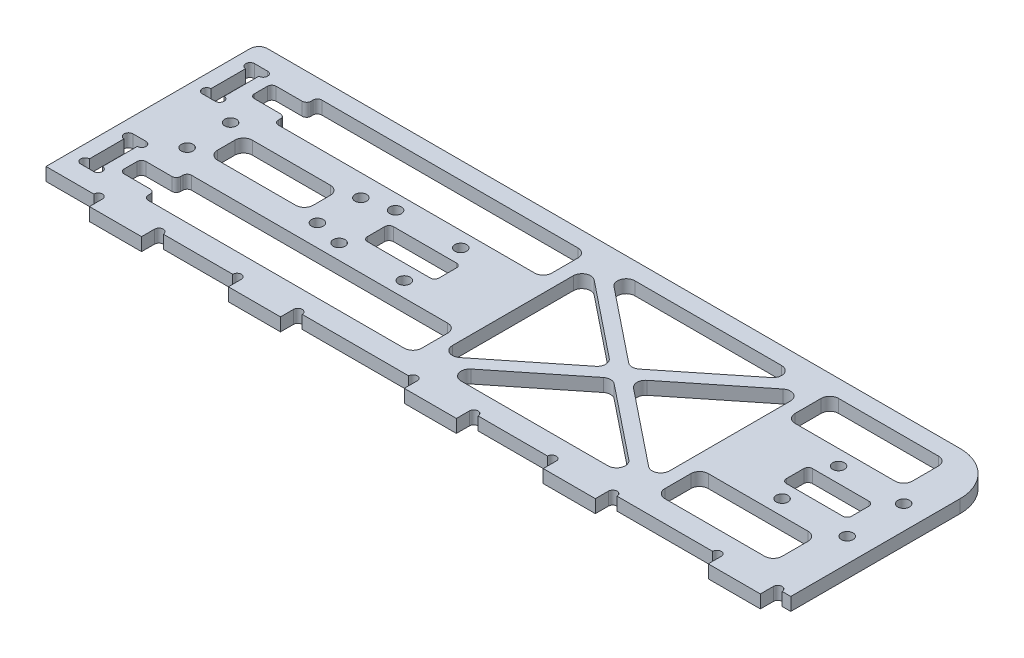
SolidWorks part; units mm, degrees
material "碳纤维"
ref_plane "前视基准面" through (0, 0, 0) normal (0, 0, 1) x (1, 0, 0)
ref_plane "上视基准面" through (0, 0, 0) normal (0, 1, 0) x (1, 0, 0)
ref_plane "右视基准面" through (0, 0, 0) normal (1, 0, 0) x (0, 0, -1)
sketch "草图1" plane through (0, 0, 0) normal (0, 1, 0) x (1, 0, 0)
  line L0 (-74, -10) -> (-12, -10)
  line L1 (-80, -24) -> (80, -24)
  line L2 (-80, -24) -> (-80, 24)
  line L3 (-80, 24) -> (80, 24)
  line L4 (80, -24) -> (80, 24)
  line L5 (0, 24) -> (0, -24) construction
  line L6 (-80, 0) -> (80, 0) construction
  line L7 (-74, 20) -> (-12, 20)
  line L8 (-74, 20) -> (-74, 10)
  line L9 (-74, 10) -> (-12, 10)
  line L10 (-12, 20) -> (-12, 10)
  line L11 (-43, 10) -> (-43, 20) construction
  line L12 (-74, 15) -> (-12, 15) construction
  line L13 (-40.5, 3) -> (-24, 3)
  line L14 (-40.5, 3) -> (-40.5, -3)
  line L15 (-40.5, -3) -> (-24, -3)
  line L16 (-24, 3) -> (-24, -3)
  line L17 (-32.25, -3) -> (-32.25, 3) construction
  line L18 (-40.5, 0) -> (-24, 0) construction
  line L19 (-12, -20) -> (-12, -10)
  line L20 (-74, -20) -> (-12, -20)
  line L21 (-74, -20) -> (-74, -10)
  line L22 (71, -10) -> (44, -10)
  line L23 (71, 20) -> (44, 20)
  line L24 (71, 20) -> (71, 10)
  line L25 (71, 10) -> (44, 10)
  line L26 (44, 20) -> (44, 10)
  line L27 (57.5, 10) -> (57.5, 20) construction
  line L28 (71, 15) -> (44, 15) construction
  line L29 (71, 3) -> (56, 3)
  line L30 (71, 3) -> (71, -3)
  line L31 (71, -3) -> (56, -3)
  line L32 (56, 3) -> (56, -3)
  line L33 (63.5, -3) -> (63.5, 3) construction
  line L34 (71, 0) -> (56, 0) construction
  line L35 (44, -20) -> (44, -10)
  line L36 (71, -20) -> (44, -20)
  line L37 (71, -20) -> (71, -10)
  point P0 (0, 0)
  point P138 (-43, 15)
  point P147 (63.5, 0)
  point P195 (-32.25, 0)
  point P297 (57.5, 15)
  dimension "D1" = 160
  dimension "D2" = 48
  dimension "D3" = 62
  dimension "D4" = 6
  dimension "D5" = 4
  dimension "D6" = 10
  dimension "D7" = 33.5
  dimension "D8" = 6
  dimension "D9" = 9
  dimension "D10" = 27
  dimension "D11" = 12
  dimension "D12" = 12
extrude "凸台-拉伸1" add sketch "草图1" along normal blind 3
sketch "草图2" plane through (0, 3, 0) normal (0, 1, 0) x (1, 0, 0)
  line L0 (80, 0) -> (-48, 0) construction
  line L1 (80, -24) -> (80, 24) construction
  line L2 (44, 15) -> (-12, 15) construction
  line L3 (44, 20) -> (44, 10) construction
  line L4 (-12, 10) -> (-12, 20) construction
  line L5 (16, 15) -> (16, 0) construction
  line L6 (67, 10) -> (67, -10) construction
  line L7 (44, 10) -> (71, 10) construction
  line L8 (71, -10) -> (44, -10) construction
  circle A0 centre (74.5, 6.5) radius 1.35
  circle A1 centre (59.5, 6.5) radius 1.35
  circle A2 centre (59.5, -6.5) radius 1.35
  circle A3 centre (74.5, -6.5) radius 1.35
  circle A4 centre (-42.5, -6.5) radius 1.35
  circle A5 centre (-27.5, -6.5) radius 1.35
  circle A6 centre (-27.5, 6.5) radius 1.35
  circle A7 centre (-42.5, 6.5) radius 1.35
  dimension "D3" = 2.7
  dimension "D1" = 15
  dimension "D2" = 13
  dimension "D4" = 51
extrude "切除-拉伸1" cut sketch "草图2" against normal through all
sketch "草图3" plane through (0, 3, 0) normal (0, 1, 0) x (1, 0, 0)
  line L0 (-80, 24) -> (-80, -24) construction
  line L1 (80, -24) -> (-80, -24)
  line L2 (80, -24) -> (80, -25)
  line L3 (80, -25) -> (-80, -25)
  line L4 (-80, -24) -> (-80, -25)
  line L5 (0, -25) -> (0, -24) construction
  line L6 (80, -24.5) -> (-80, -24.5) construction
  point P196 (0, -24.5)
  dimension "D1" = 1
extrude "凸台-拉伸2" add sketch "草图3" against normal blind 3
sketch "草图5" plane through (0, 3, 0) normal (0, 1, 0) x (1, 0, 0)
  line L0 (80, 24) -> (-80, 24) construction
  line L1 (-80, -25) -> (-85, -25)
  line L2 (-80, -25) -> (-80, 24)
  line L3 (-80, 24) -> (-85, 24)
  line L4 (-85, -25) -> (-85, 24)
  line L5 (-82.5, 24) -> (-82.5, -25) construction
  line L6 (-80, -0.5) -> (-85, -0.5) construction
  point P104 (-82.5, -0.5)
  dimension "D1" = 5
extrude "凸台-拉伸4" add sketch "草图5" against normal up to surface (3 mm away) up to face at (-42.5, 0, 7.85)
sketch "草图6" plane through (0, 3, 0) normal (0, 1, 0) x (1, 0, 0)
  line L0 (-74, -10) -> (-74, -20) construction
  line L1 (-74, -17.5) -> (-82, -17.5)
  line L2 (-74, -17.5) -> (-74, -12.5)
  line L3 (-74, -12.5) -> (-82, -12.5)
  line L4 (-82, -17.5) -> (-82, -12.5)
  line L5 (-78, -12.5) -> (-78, -17.5) construction
  line L6 (-74, -15) -> (-82, -15) construction
  line L7 (-12, -15) -> (-12, 15) construction
  line L8 (-12, -20) -> (-12, -10) construction
  line L9 (-12, 10) -> (-12, 20) construction
  line L10 (-12, 0) -> (-85, 0) construction
  line L12 (-74, 12.5) -> (-82, 12.5)
  line L13 (-82, 17.5) -> (-82, 12.5)
  line L14 (-74, 17.5) -> (-82, 17.5)
  line L15 (-74, 17.5) -> (-74, 12.5)
  line L16 (-85, 24) -> (-85, -25) construction
  point P96 (-78, -15)
  dimension "D1" = 8
  dimension "D2" = 5
extrude "切除-拉伸2" cut sketch "草图6" against normal through all
sketch "草图7" plane through (0, 3, 0) normal (0, 1, 0) x (1, 0, 0)
  line L0 (-85, -25) -> (80, -25) construction
  line L1 (76, -25) -> (64, -25)
  line L2 (76, -25) -> (76, -28)
  line L3 (76, -28) -> (64, -28)
  line L4 (64, -25) -> (64, -28)
  line L5 (70, -28) -> (70, -25) construction
  line L6 (76, -26.5) -> (64, -26.5) construction
  line L7 (80, -25) -> (80, 24) construction
  line L8 (44, -15) -> (-12, -15) construction
  line L9 (44, -10) -> (44, -20) construction
  line L10 (-12, -20) -> (-12, -10) construction
  line L11 (16, -15) -> (16, -25) construction
  line L12 (-6, -28) -> (6, -28)
  line L13 (38, -25) -> (26, -25)
  line L14 (38, -25) -> (38, -28)
  line L15 (38, -28) -> (26, -28)
  line L16 (26, -25) -> (26, -28)
  line L17 (32, -28) -> (32, -25) construction
  line L18 (38, -26.5) -> (26, -26.5) construction
  line L19 (6, -25) -> (6, -28)
  line L20 (-6, -25) -> (6, -25)
  line L21 (-6, -25) -> (-6, -28)
  line L22 (-56.5, -25) -> (-56.5, 24) construction
  line L23 (-85, -25) -> (80, -25) construction
  line L24 (80, 24) -> (-85, 24) construction
  line L25 (-85, 24) -> (-85, -25) construction
  line L26 (-78.5, -28) -> (-66.5, -28)
  line L27 (-34.5, -25) -> (-46.5, -25)
  line L28 (-34.5, -25) -> (-34.5, -28)
  line L29 (-34.5, -28) -> (-46.5, -28)
  line L30 (-46.5, -25) -> (-46.5, -28)
  line L31 (-40.5, -28) -> (-40.5, -25) construction
  line L32 (-34.5, -26.5) -> (-46.5, -26.5) construction
  line L33 (-66.5, -25) -> (-66.5, -28)
  line L34 (-78.5, -25) -> (-66.5, -25)
  line L35 (-78.5, -25) -> (-78.5, -28)
  point P76 (70, -26.5)
  point P93 (32, -26.5)
  point P138 (-40.5, -26.5)
  dimension "D1" = 12
  dimension "D2" = 10
  dimension "D3" = 3
  dimension "D4" = 12
  dimension "D5" = 3
  dimension "D6" = 20
  dimension "D7" = 28.5
  dimension "D8" = 12
  dimension "D9" = 20
extrude "凸台-拉伸5" add sketch "草图7" against normal up to surface (3 mm away) up to face at (-60.5, 0, 15)
sketch "草图9" plane through (0, 3, 0) normal (0, 1, 0) x (1, 0, 0)
  line L0 (-85, 24) -> (-85, -25) construction
  line L1 (-85, -20.5) -> (-88, -20.5)
  line L2 (-85, -20.5) -> (-85, -8.5)
  line L3 (-85, -8.5) -> (-88, -8.5)
  line L4 (-88, -20.5) -> (-88, -8.5)
  line L5 (-86.5, -8.5) -> (-86.5, -20.5) construction
  line L6 (-85, -14.5) -> (-88, -14.5) construction
  line L7 (-85, -0.5) -> (80, -0.5) construction
  line L8 (80, -25) -> (80, 24) construction
  line L9 (-85, 7.5) -> (-88, 7.5)
  line L10 (-88, 19.5) -> (-88, 7.5)
  line L11 (-85, 19.5) -> (-88, 19.5)
  line L12 (-85, 19.5) -> (-85, 7.5)
  line L13 (80, 24) -> (-85, 24) construction
  line L14 (-85, -25) -> (-91.5, -25)
  line L15 (-85, -25) -> (-85, 24)
  line L16 (-85, 24) -> (-91.5, 24)
  line L17 (-91.5, -25) -> (-91.5, 24)
  point P168 (-86.5, -14.5)
  dimension "D1" = 12
  dimension "D2" = 3
  dimension "D3" = 28
  dimension "D4" = 3.5
extrude "凸台-拉伸6" add sketch "草图9" against normal up to surface (3 mm away) contours L17 L14 L15 L1 L4 L3 L9 L10 L11 L16 up to face at (-60.5, 0, 15)
sketch "草图8" plane through (0, 3, 0) normal (0, 1, 0) x (1, 0, 0)
  line L0 (38, -25) -> (64, -25) construction
  line L1 (76, -25) -> (80, -25) construction
  line L2 (38, -25) -> (64, -25) construction
  line L3 (6, -25) -> (26, -25) construction
  line L4 (-34.5, -25) -> (-6, -25) construction
  line L5 (-20.25, -25) -> (-20.25, -20) construction
  line L6 (-34.5, -25) -> (-6, -25) construction
  line L7 (-74, -20) -> (-12, -20) construction
  line L8 (-56.5, -25) -> (-56.5, -20) construction
  line L9 (-66.5, -25) -> (-46.5, -25) construction
  line L11 (-88, -14.5) -> (-82, -14.5) construction
  line L13 (-82, -12.5) -> (-82, -17.5) construction
  line L14 (-85, -0.5) -> (-40.5, -0.5) construction
  line L15 (-85, 7.5) -> (-85, -8.5) construction
  line L16 (-40.5, 3) -> (-40.5, -3) construction
  line L17 (-86.5, -8.5) -> (-86.5, -14.5) construction
  line L18 (-85, -8.5) -> (-88, -8.5) construction
  line L19 (-85, -8.5) -> (-85, -20.5) construction
  line L20 (-85, -20.5) -> (-88, -20.5) construction
  line L21 (-88, -20.5) -> (-88, -8.5) construction
  circle A0 centre (63, -25) radius 1
  circle A1 centre (77, -25) radius 1
  circle A2 centre (39, -25) radius 1
  circle A3 centre (25, -25) radius 1
  circle A4 centre (7, -25) radius 1
  circle A5 centre (-7, -25) radius 1
  circle A6 centre (-33.5, -25) radius 1
  circle A7 centre (-47.5, -25) radius 1
  circle A8 centre (-65.5, -25) radius 1
  circle A9 centre (-79.5, -25) radius 1
  circle A14 centre (-85, -19.5) radius 1
  circle A15 centre (-88, -19.5) radius 1
  circle A16 centre (-88, -9.5) radius 1
  circle A17 centre (-85, -9.5) radius 1
  circle A18 centre (-85, 8.5) radius 1
  circle A19 centre (-88, 8.5) radius 1
  circle A20 centre (-88, 18.5) radius 1
  circle A21 centre (-85, 18.5) radius 1
  dimension "D1" = 2
extrude "切除-拉伸3" cut sketch "草图8" against normal through all
sketch "草图12" plane through (0, 3, 0) normal (0, 1, 0) x (1, 0, 0)
  line L0 (-49, 0) -> (-40.5, 0) construction
  line L2 (-40.5, 3) -> (-40.5, -3) construction
  line L3 (-49, 5) -> (-79, 5) construction
  line L4 (-49, 5) -> (-49, -5) construction
  line L5 (-49, -5) -> (-79, -5) construction
  line L6 (-79, 5) -> (-79, -5) construction
  line L7 (-64, -5) -> (-64, 5) construction
  line L8 (-49, 0) -> (-79, 0) construction
  line L10 (-91.5, -25) -> (-91.5, 24) construction
  circle A0 centre (-79, -5) radius 1.35
  circle A1 centre (-79, 5) radius 1.35
  circle A2 centre (-49, 5) radius 1.35
  circle A3 centre (-49, -5) radius 1.35
  dimension "D2" = 2.7
  dimension "D4" = 12.5
  dimension "D1" = 10
  dimension "D3" = 30
extrude "切除-拉伸6" cut sketch "草图12" against normal through all
sketch "草图11" plane through (0, 3, 0) normal (0, 1, 0) x (1, 0, 0)
  line L0 (-74, -20) -> (-12, -20) construction
  line L1 (41, -20) -> (-9, -20) construction
  line L2 (41, -20) -> (41, 20) construction
  line L3 (41, 20) -> (-9, 20) construction
  line L4 (-9, -20) -> (-9, 20) construction
  line L5 (16, 20) -> (16, -20) construction
  line L6 (41, 0) -> (-9, 0) construction
  line L7 (-12, 20) -> (-74, 20) construction
  line L8 (-12, -20) -> (-12, -10) construction
  line L9 (44, -10) -> (44, -20) construction
  line L10 (38.5988, -20) -> (16, -1.9209)
  line L11 (16, -1.9209) -> (-6.5988, -20)
  line L12 (-6.5988, -20) -> (38.5988, -20)
  line L13 (41, -18.0791) -> (41, 18.0791)
  line L14 (41, 18.0791) -> (18.4012, 0)
  line L15 (18.4012, 0) -> (41, -18.0791)
  line L16 (41, -20) -> (16, 0) construction
  line L17 (16, 1.9209) -> (-6.5988, 20)
  line L18 (38.5988, 20) -> (16, 1.9209)
  line L19 (-6.5988, 20) -> (38.5988, 20)
  line L20 (-9, 18.0791) -> (13.5988, 0)
  line L21 (-9, -18.0791) -> (-9, 18.0791)
  line L22 (13.5988, 0) -> (-9, -18.0791)
  line L24 (-53, -4) -> (-75, -4)
  line L25 (-53, -4) -> (-53, 4)
  line L26 (-53, 4) -> (-75, 4)
  line L27 (-75, -4) -> (-75, 4)
  line L28 (-64, 4) -> (-64, -4) construction
  line L29 (-53, 0) -> (-75, 0) construction
  line L30 (-79, -5) -> (-49, -5) construction
  line L31 (-64, -5) -> (-64, -4) construction
  line L32 (-12, -10) -> (-74, -10) construction
  line L33 (-74, 10) -> (-12, 10) construction
  point P189 (-64, 0)
  point P196 (16, 0)
  dimension "D1" = 3
  dimension "D2" = 3
  dimension "D3" = 3
  dimension "D4" = 22
  dimension "D5" = 6
  dimension "D6" = 6
extrude "切除-拉伸5" cut sketch "草图11" against normal through all
sketch "草图13" plane through (0, 3, 0) normal (0, 1, 0) x (1, 0, 0)
  line L4 (-91.5, -0.5) -> (-75, -0.5) construction
  line L8 (-84.98, -18.4802) -> (-84.98, -10.5198)
  line L9 (-85, -8.48) -> (-88, -8.48)
  line L10 (-88.02, -10.5198) -> (-88.02, -18.4802)
  line L11 (-88, -20.52) -> (-85, -20.52)
  line L12 (-84.98, -18.4802) -> (-84.98, -10.5198)
  line L13 (-85, -8.48) -> (-88, -8.48)
  line L14 (-88.02, -10.5198) -> (-88.02, -18.4802)
  line L15 (-88, -20.52) -> (-85, -20.52)
  line L19 (-91.5, -25) -> (-91.5, 24) construction
  line L20 (-75, 4) -> (-75, -4) construction
  line L21 (-88, 19.52) -> (-85, 19.52)
  line L22 (-88.02, 9.5198) -> (-88.02, 17.4802)
  line L23 (-85, 7.48) -> (-88, 7.48)
  line L24 (-84.98, 17.4802) -> (-84.98, 9.5198)
  arc A8 (-85, -20.52) -> (-84.98, -18.4802) centre (-85, -19.5) ccw
  arc A9 (-84.98, -10.5198) -> (-85, -8.48) centre (-85, -9.5) ccw
  arc A10 (-88, -8.48) -> (-88.02, -10.5198) centre (-88, -9.5) ccw
  arc A11 (-88.02, -18.4802) -> (-88, -20.52) centre (-88, -19.5) ccw
  arc A12 (-85, -20.52) -> (-84.98, -18.4802) centre (-85, -19.5) ccw
  arc A13 (-84.98, -10.5198) -> (-85, -8.48) centre (-85, -9.5) ccw
  arc A14 (-88, -8.48) -> (-88.02, -10.5198) centre (-88, -9.5) ccw
  arc A15 (-88.02, -18.4802) -> (-88, -20.52) centre (-88, -19.5) ccw
  arc A16 (-88.02, 17.4802) -> (-88, 19.52) centre (-88, 18.5) cw
  arc A17 (-88, 7.48) -> (-88.02, 9.5198) centre (-88, 8.5) cw
  arc A18 (-84.98, 9.5198) -> (-85, 7.48) centre (-85, 8.5) cw
  arc A19 (-85, 19.52) -> (-84.98, 17.4802) centre (-85, 18.5) cw
  dimension "D1" = 0.02
extrude "余量" cut sketch "草图13" against normal through all
fillet "圆角2" radius 2 12 edges at (71, 1.5, 10) (44, 1.5, 10) (44, 1.5, 20) (71, 1.5, 20) (-12, 1.5, 20) (-12, 1.5, -10) (-12, 1.5, -20) (71, 1.5, -20) (44, 1.5, -20) (44, 1.5, -10) (71, 1.5, -10) (-12, 1.5, 10)
fillet "圆角1" radius 1 20 edges at (-74, 1.5, -20) (-74, 1.5, -17.5) (-82, 1.5, -17.5) (-82, 1.5, -12.5) (-74, 1.5, -12.5) (-74, 1.5, -10) (-82, 1.5, 17.5) (-82, 1.5, 12.5) (-74, 1.5, 10) (-74, 1.5, 12.5) (-74, 1.5, 17.5) (-74, 1.5, 20) (71, 1.5, -3) (56, 1.5, -3) (71, 1.5, 3) (56, 1.5, 3) (-24, 1.5, 3) (-24, 1.5, -3) (-40.5, 1.5, -3) (-40.5, 1.5, 3)
fillet "圆角3" radius 10 1 edges at (80, 1.5, -24)
fillet "圆角4" radius 2 17 edges at (16, 1.5, 1.9209) (38.5988, 1.5, 20) (-9, 1.5, -18.0791) (13.5988, 1.5, 0) (-9, 1.5, 18.0791) (18.4012, 1.5, 0) (41, 1.5, -18.0791) (41, 1.5, 18.0791) (16, 1.5, -1.9209) (-6.5988, 1.5, -20) (38.5988, 1.5, -20) (-6.5988, 1.5, 20) (-53, 1.5, 4) (-75, 1.5, -4) (-53, 1.5, -4) (-75, 1.5, 4) (-91.5, 1.5, -24)
move or copy body "实体-移动/复制1" [suppressed] bodies to move or copy 115
